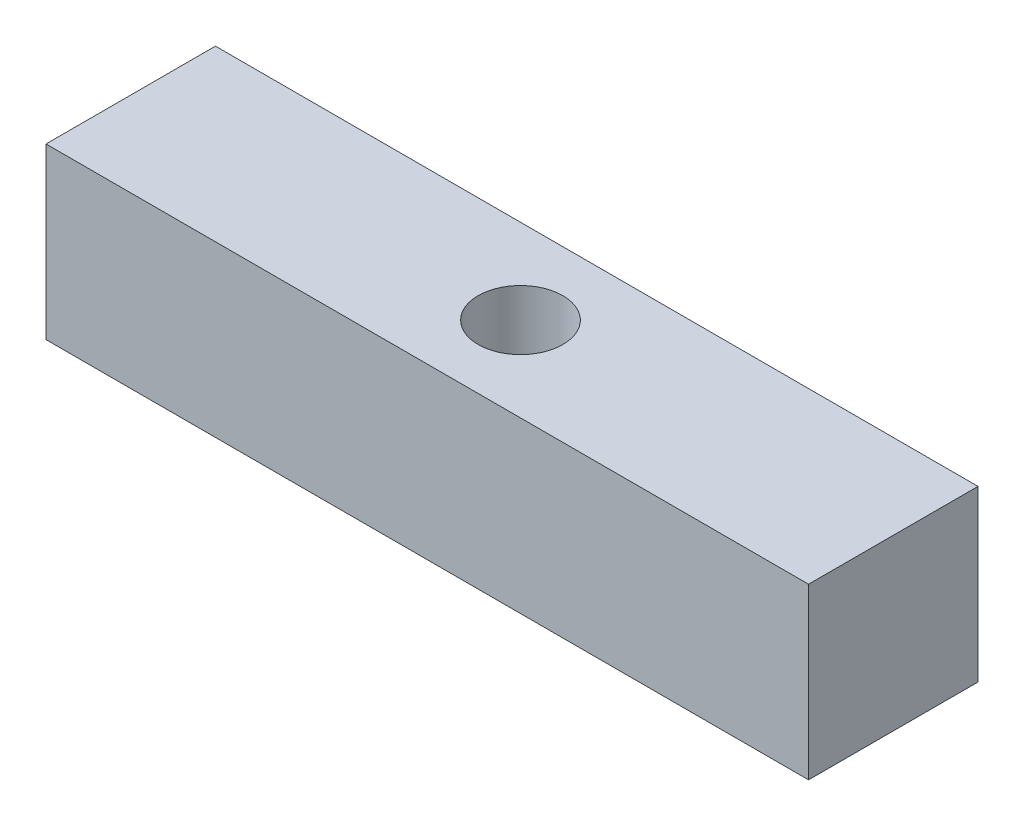
SolidWorks part; units mm, degrees
ref_plane "Piano frontale" through (0, 0, 0) normal (0, 0, 1) x (1, 0, 0)
ref_plane "Piano superiore" through (0, 0, 0) normal (0, 1, 0) x (1, 0, 0)
ref_plane "Piano destro" through (0, 0, 0) normal (1, 0, 0) x (0, 0, -1)
sketch "Schizzo1" plane through (0, 0, 0) normal (0, 0, 1) x (1, 0, 0)
  line L0 (22.5, -41.5841) -> (22.5, 4.4159) construction
  line L1 (-22.5, -41.5841) -> (22.5, -41.5841)
  line L2 (-22.5, -41.5841) -> (-22.5, -31.5841)
  line L3 (-22.5, -31.5841) -> (22.5, -31.5841)
  line L4 (22.5, -41.5841) -> (22.5, -31.5841)
  dimension "D1" = 10
extrude "Estrusione-Estrusione1" add sketch "Schizzo1" along normal mid plane 10
sketch "Schizzo2" plane through (0, -41.5841, 0) normal (0, -1, 0) x (1, 0, 0)
  circle A0 centre (0.5011, 0) radius 2.5
  dimension "D1" = 5
extrude "Taglio-Estrusione1" cut sketch "Schizzo2" against normal through all
cosmetic thread "Filettatura cosmetica2" parameters "D2"=6
